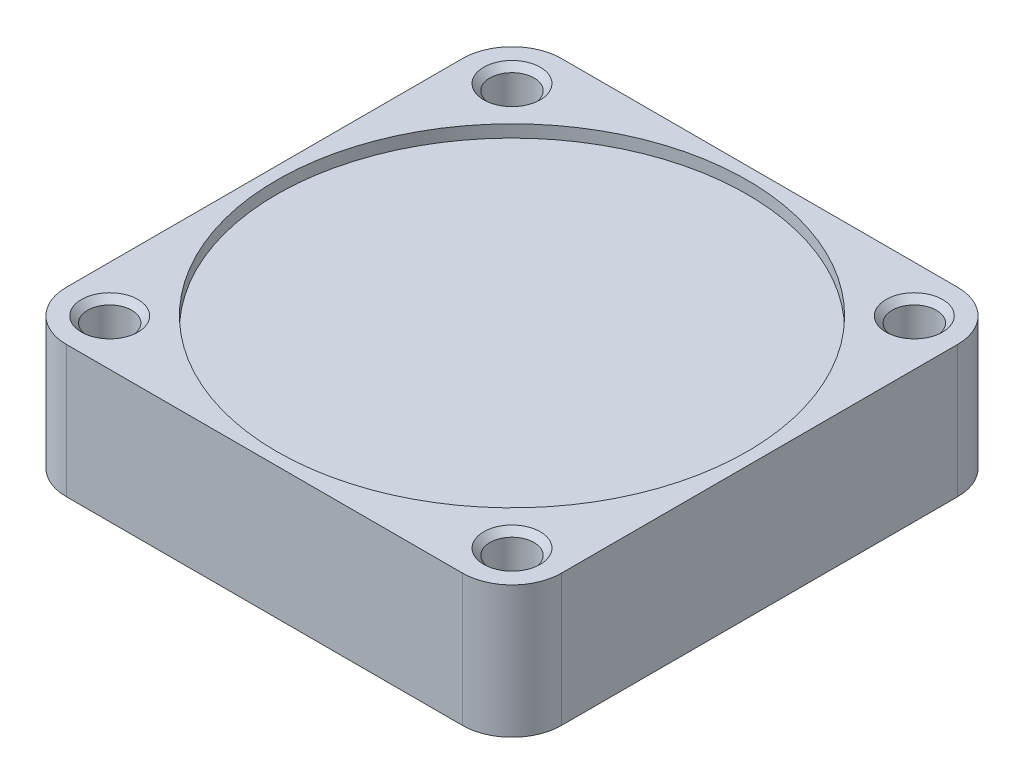
SolidWorks part; units mm, degrees
ref_plane "Front Plane" through (0, 0, 0) normal (0, 0, 1) x (1, 0, 0)
ref_plane "Top Plane" through (0, 0, 0) normal (0, 1, 0) x (1, 0, 0)
ref_plane "Right Plane" through (0, 0, 0) normal (1, 0, 0) x (0, 0, -1)
sketch "Sketch1" plane through (0, 0, 0) normal (0, 1, 0) x (1, 0, 0)
  line L1 (0, 0) -> (-40, 0)
  line L2 (0, 0) -> (0, 40)
  line L3 (0, 40) -> (-40, 40)
  line L4 (-40, 0) -> (-40, 40)
  dimension "D1" = 40
  dimension "D2" = 40
extrude "Boss-Extrude1" add sketch "Sketch1" along normal blind 10.66
sketch "Sketch2" plane through (0, 10.66, 0) normal (0, 1, 0) x (1, 0, 0)
  line L0 (-40, 40) -> (0, 0) construction
  circle A0 centre (-20, 20) radius 19
  point P6 (-20, 20)
  dimension "D1" = 38
sketch "Sketch3" plane through (0, 0, 0) normal (0, -1, 0) x (1, 0, 0)
  circle A0 centre (-20, -20) radius 19
extrude "Cut-Extrude1" cut sketch "Sketch2" against normal blind 1 contours A0
extrude "Cut-Extrude2" cut sketch "Sketch3" against normal blind 1 contours A0
sketch "Sketch4" plane through (0, 10.66, 0) normal (0, 1, 0) x (1, 0, 0)
  line L0 (0, 40) -> (-40, 40) construction
  line L1 (-40, 40) -> (-40, 0) construction
  circle A0 centre (-36.25, 36.25) radius 1.785
  circle A1 centre (-20, 20) radius 19 construction
  circle A2 centre (-3.75, 36.25) radius 1.785
  circle A3 centre (-3.75, 3.75) radius 1.785
  circle A4 centre (-36.25, 3.75) radius 1.785
  point P7 (-20, 20)
  point P18 (-20, 20)
  dimension "D1" = 3.57
  dimension "D2" = 3.75
  dimension "D3" = 3.75
  dimension "D4" = 4
sketch "Sketch5" plane through (0, 0, 0) normal (0, -1, 0) x (1, 0, 0)
  line L0 (-39.019, -34.6261) -> (-39.0409, -37.8361)
  line L1 (-34.6261, -0.981) -> (-37.8361, -0.9591)
  line L2 (-37.8361, -0.9591) -> (-39.46, -3.7282)
  line L3 (-39.46, -3.7282) -> (-37.8739, -6.519)
  line L4 (-37.8739, -6.519) -> (-34.6639, -6.5409)
  line L5 (-34.6639, -6.5409) -> (-33.04, -3.7718)
  line L6 (-33.04, -3.7718) -> (-34.6261, -0.981)
  line L7 (-39.0409, -37.8361) -> (-36.2718, -39.46)
  line L8 (-36.2718, -39.46) -> (-33.481, -37.8739)
  line L9 (-33.481, -37.8739) -> (-33.4591, -34.6639)
  line L10 (-33.4591, -34.6639) -> (-36.2282, -33.04)
  line L11 (-36.2282, -33.04) -> (-39.019, -34.6261)
  line L12 (-5.3739, -39.019) -> (-2.1639, -39.0409)
  line L13 (-2.1639, -39.0409) -> (-0.54, -36.2718)
  line L14 (-0.54, -36.2718) -> (-2.1261, -33.481)
  line L15 (-2.1261, -33.481) -> (-5.3361, -33.4591)
  line L16 (-5.3361, -33.4591) -> (-6.96, -36.2282)
  line L17 (-6.96, -36.2282) -> (-5.3739, -39.019)
  line L18 (-0.981, -5.3739) -> (-0.9591, -2.1639)
  line L19 (-0.9591, -2.1639) -> (-3.7282, -0.54)
  line L20 (-3.7282, -0.54) -> (-6.519, -2.1261)
  line L21 (-6.519, -2.1261) -> (-6.5409, -5.3361)
  line L22 (-6.5409, -5.3361) -> (-3.7718, -6.96)
  line L23 (-3.7718, -6.96) -> (-0.981, -5.3739)
  circle A0 centre (-36.25, -3.75) radius 2.78 construction
  circle A1 centre (-36.25, -36.25) radius 2.78 construction
  circle A2 centre (-3.75, -36.25) radius 2.78 construction
  circle A3 centre (-3.75, -3.75) radius 2.78 construction
  point P36 (-20, -20)
  dimension "D1" = 5.56
  dimension "D2" = 4
extrude "Cut-Extrude3" cut sketch "Sketch4" against normal through all
extrude "Cut-Extrude4" cut sketch "Sketch5" against normal blind 3.25
chamfer "Chamfer1" distance 0.5 angle 45 4 edges at (-3.75, 10.66, -1.965) (-36.25, 10.66, -1.965) (-36.25, 10.66, -34.465) (-3.75, 10.66, -34.465)
fillet "Fillet1" radius 4 4 edges at (-40, 5.33, 0) (0, 5.33, 0) (0, 5.33, -40) (-40, 5.33, -40)
equation "\"4.00.00mm\"=400"
